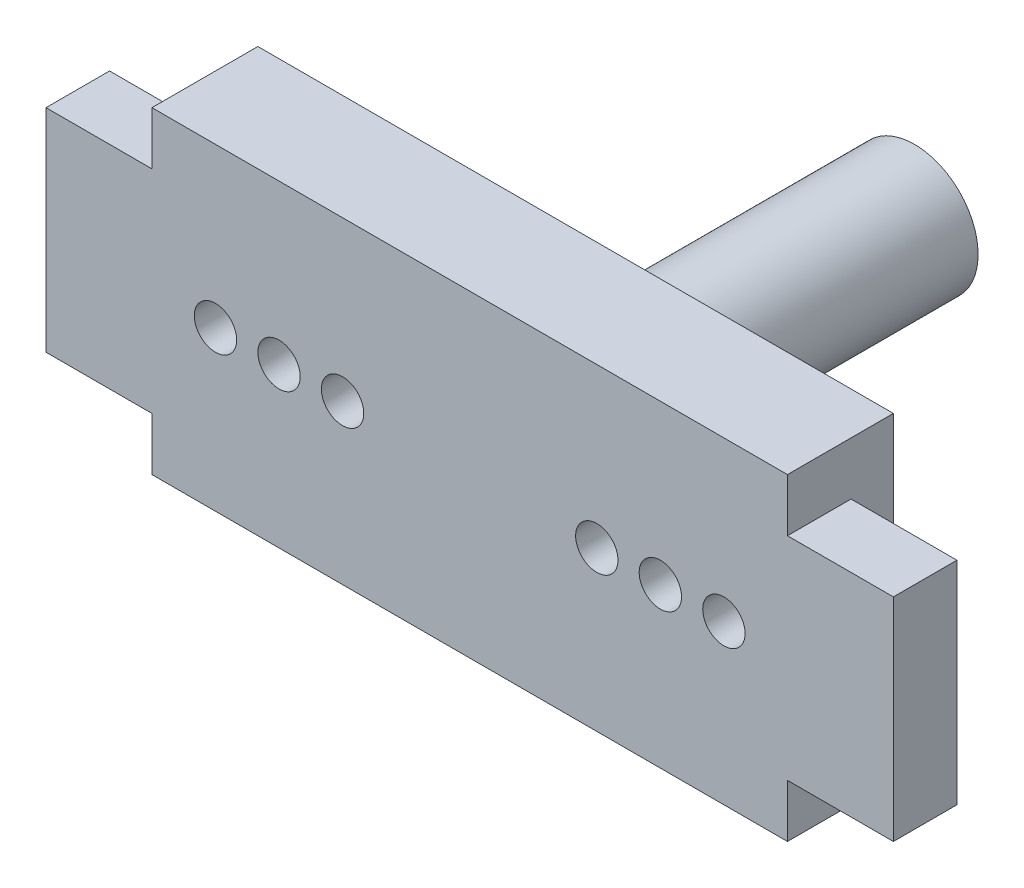
SolidWorks part; units mm, degrees
ref_plane "Front Plane" through (0, 0, 0) normal (0, 0, 1) x (1, 0, 0)
ref_plane "Top Plane" through (0, 0, 0) normal (0, 1, 0) x (1, 0, 0)
ref_plane "Right Plane" through (0, 0, 0) normal (1, 0, 0) x (0, 0, -1)
sketch "Sketch1" plane through (0, 0, 0) normal (0, 1, 0) x (1, 0, 0)
  line L1 (-61.8805, -26.2097) -> (-56.8805, -26.2097)
  line L2 (-61.8805, -26.2097) -> (-61.8805, 28.7903)
  line L3 (-61.8805, 28.7903) -> (-56.8805, 28.7903)
  line L4 (-56.8805, -26.2097) -> (-56.8805, 28.7903)
  line L5 (-56.8805, 28.7903) -> (-26.8805, 28.7903)
  line L6 (-56.8805, 28.7903) -> (-56.8805, 23.7903)
  line L7 (-56.8805, 23.7903) -> (-26.8805, 23.7903)
  line L8 (-26.8805, 28.7903) -> (-26.8805, 23.7903)
  line L9 (-26.8805, 28.7903) -> (-21.8805, 28.7903)
  line L10 (-26.8805, 28.7903) -> (-26.8805, -26.2097)
  line L11 (-26.8805, -26.2097) -> (-21.8805, -26.2097)
  line L12 (-21.8805, 28.7903) -> (-21.8805, -26.2097)
  dimension "D1" = 30
  dimension "D2" = 5
  dimension "D3" = 50
  dimension "D4" = 50
  dimension "D5" = 5
  dimension "D6" = 5
extrude "Boss-Extrude1" add sketch "Sketch1" along normal blind 15 contours L8 L5 L4 L7 | L10 L9 L12 L11
sketch "Sketch3" plane through (0, 0, -28.7903) normal (0, 0, -1) x (-1, 0, 0)
  line L0 (41.8805, 0) -> (41.8805, 15) construction
  line L1 (56.8805, 0) -> (26.8805, 0) construction
  line L2 (56.8805, 15) -> (26.8805, 15) construction
  circle A0 centre (35.8805, 7.5) radius 1
  circle A1 centre (32.8805, 7.5) radius 1
  circle A2 centre (29.8805, 7.5) radius 1
  circle A3 centre (53.8805, 7.5) radius 1
  circle A4 centre (50.8805, 7.5) radius 1
  circle A5 centre (47.8805, 7.5) radius 1
  dimension "D5" = 2
  dimension "D6" = 12
  dimension "D1" = 2
  dimension "D2" = 6
  dimension "D4" = 9
  dimension "D3" = 7.5
extrude "Cut-Extrude2" cut sketch "Sketch3" against normal up to surface (5 mm away) up to face at (-41.8805, 7.5, -23.7903)
sketch "Sketch4" plane through (0, 0, -28.7903) normal (0, 0, -1) x (-1, 0, 0)
  line L2 (56.8805, 0) -> (26.8805, 0) construction
  line L3 (26.8805, 15) -> (26.8805, 0) construction
  circle A0 centre (41.8805, 7.5) radius 3
  dimension "D3" = 6
  dimension "D1" = 7.5
  dimension "D2" = 15
sketch "Sketch5" plane through (0, 0, -23.7903) normal (0, 0, 1) x (1, 0, 0)
  line L0 (-56.8805, 15) -> (-56.8805, 0) construction
  line L1 (-56.8805, 12.5) -> (-61.8805, 12.5)
  line L2 (-56.8805, 12.5) -> (-56.8805, 2.5)
  line L3 (-56.8805, 2.5) -> (-61.8805, 2.5)
  line L4 (-61.8805, 12.5) -> (-61.8805, 2.5)
  line L5 (-56.8805, 15) -> (-26.8805, 15) construction
  line L6 (-56.8805, 0) -> (-26.8805, 0) construction
  line L7 (-41.8805, 15) -> (-41.8805, 0) construction
  line L8 (-26.8805, 2.5) -> (-21.8805, 2.5)
  line L9 (-21.8805, 12.5) -> (-21.8805, 2.5)
  line L10 (-26.8805, 12.5) -> (-21.8805, 12.5)
  line L11 (-26.8805, 12.5) -> (-26.8805, 2.5)
  dimension "D1" = 2.5
  dimension "D2" = 2.5
  dimension "D3" = 5
extrude "Boss-Extrude2" add sketch "Sketch5" against normal blind 3 contours L2 L1 L4 L3 | L8 L9 L10 L11
extrude "Boss-Extrude3" add sketch "Sketch4" along normal blind 16
